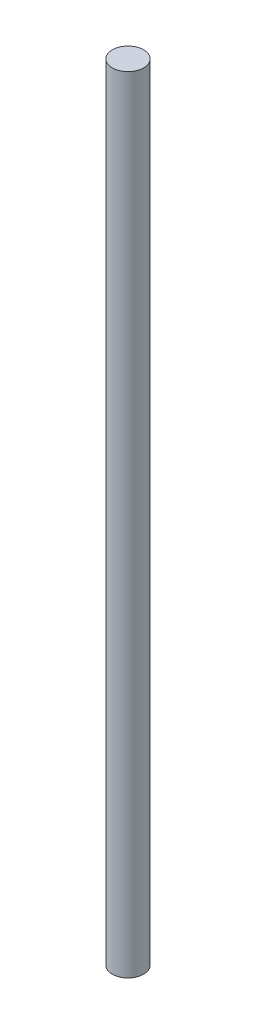
SolidWorks part; units mm, degrees
ref_plane "前视基准面" through (0, 0, 0) normal (0, 0, 1) x (1, 0, 0)
ref_plane "上视基准面" through (0, 0, 0) normal (0, 1, 0) x (1, 0, 0)
ref_plane "右视基准面" through (0, 0, 0) normal (1, 0, 0) x (0, 0, -1)
sketch "草图1" plane through (0, 0, 0) normal (0, 1, 0) x (1, 0, 0)
  circle A0 centre (0, 0) radius 10
  dimension "D1" = 20
extrude "凸台-拉伸1" add sketch "草图1" along normal blind 500
